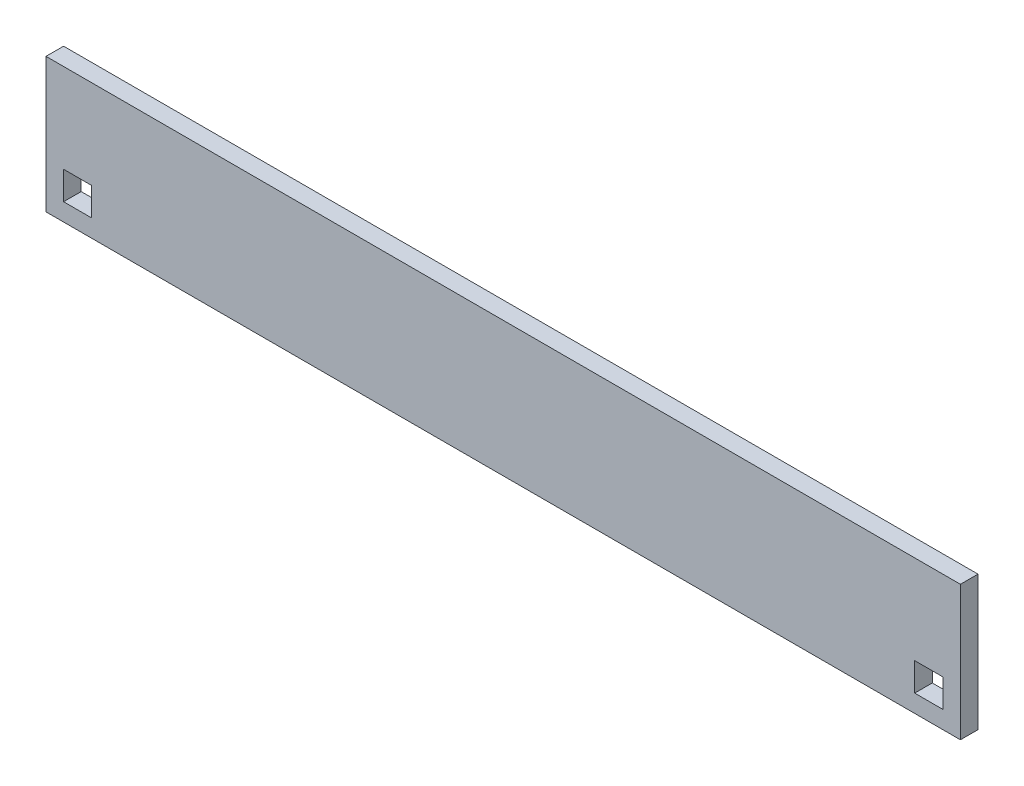
SolidWorks part; units mm, degrees
ref_plane "Alzado" through (0, 0, 0) normal (0, 0, 1) x (1, 0, 0)
ref_plane "Planta" through (0, 0, 0) normal (0, 1, 0) x (1, 0, 0)
ref_plane "Vista lateral" through (0, 0, 0) normal (1, 0, 0) x (0, 0, -1)
sketch "Croquis1" plane through (0, 0, 0) normal (0, 0, 1) x (1, 0, 0)
  line L1 (0, 0) -> (260, 0)
  line L2 (0, 0) -> (0, 38.3035)
  line L3 (0, 38.3035) -> (260, 38.3035)
  line L4 (260, 0) -> (260, 38.3035)
  dimension "D1" = 38.3035
  dimension "D2" = 260
extrude "Saliente-Extruir1" add sketch "Croquis1" along normal blind 5
sketch "Croquis2" plane through (0, 0, 5) normal (0, 0, 1) x (1, 0, 0)
  line L0 (0, 38.3035) -> (0, 0) construction
  line L1 (5, 13) -> (13, 13)
  line L2 (5, 13) -> (5, 5)
  line L3 (5, 5) -> (13, 5)
  line L4 (13, 13) -> (13, 5)
  line L5 (0, 0) -> (260, 0) construction
  line L6 (130, 38.3035) -> (130, 11.8564) construction
  line L7 (260, 38.3035) -> (0, 38.3035) construction
  line L8 (255, 5) -> (247, 5)
  line L9 (255, 13) -> (255, 5)
  line L10 (255, 13) -> (247, 13)
  line L11 (247, 13) -> (247, 5)
  dimension "D1" = 8
  dimension "D2" = 8
  dimension "D3" = 5
  dimension "D4" = 5
extrude "Cortar-Extruir1" cut sketch "Croquis2" against normal blind 10
sketch "Croquis3" plane through (0, 0, 5) normal (0, 0, 1) x (1, 0, 0)
  line L4 (0, 38.3035) -> (0, 0)
  line L5 (0, 0) -> (260, 0)
  line L6 (260, 0) -> (260, 38.3035)
  line L7 (260, 38.3035) -> (0, 38.3035)
  line L8 (0, 38.3035) -> (0, 0)
  line L9 (0, 0) -> (260, 0)
  line L10 (260, 0) -> (260, 38.3035)
  line L11 (260, 38.3035) -> (0, 38.3035)
  line L12 (255, 13) -> (247, 13)
  line L13 (255, 5) -> (255, 13)
  line L14 (247, 5) -> (255, 5)
  line L15 (247, 13) -> (247, 5)
  line L16 (255, 13) -> (247, 13)
  line L17 (255, 5) -> (255, 13)
  line L18 (247, 5) -> (255, 5)
  line L19 (247, 13) -> (247, 5)
  line L20 (5, 5) -> (13, 5)
  line L21 (5, 13) -> (5, 5)
  line L22 (13, 13) -> (5, 13)
  line L23 (13, 5) -> (13, 13)
  line L24 (5, 5) -> (13, 5)
  line L25 (5, 13) -> (5, 5)
  line L26 (13, 13) -> (5, 13)
  line L27 (13, 5) -> (13, 13)
  dimension "D1" = 0
  dimension "D2" = 0
  dimension "D3" = 0
